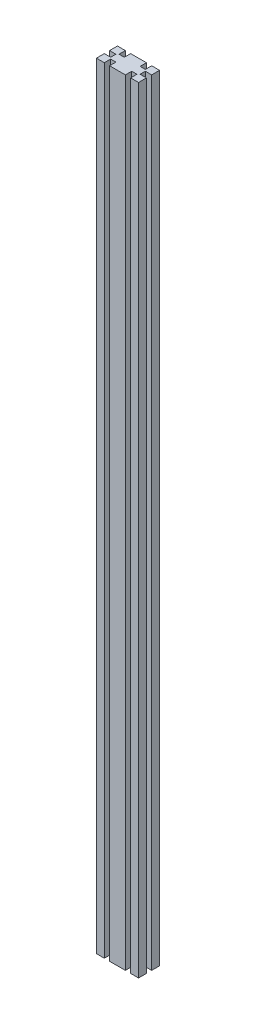
SolidWorks part; units mm, degrees
ref_plane "Front Plane" through (0, 0, 0) normal (0, 0, 1) x (1, 0, 0)
ref_plane "Top Plane" through (0, 0, 0) normal (0, 1, 0) x (1, 0, 0)
ref_plane "Right Plane" through (0, 0, 0) normal (1, 0, 0) x (0, 0, -1)
sketch "Sketch1" plane through (0, 0, 0) normal (0, 1, 0) x (1, 0, 0)
  line L1 (-20, -10) -> (20, -10)
  line L2 (-20, -10) -> (-20, 10)
  line L3 (-20, 10) -> (20, 10)
  line L4 (20, -10) -> (20, 10)
  line L5 (-20, -10) -> (20, 10) construction
  line L6 (-20, 10) -> (20, -10) construction
  point P0 (0, 0)
  dimension "D1" = 20
  dimension "D2" = 40
extrude "Boss-Extrude1" add sketch "Sketch1" along normal blind 368.3 and the other way blind 368.3
sketch "Sketch2" plane through (0, 0, 0) normal (0, 1, 0) x (1, 0, 0)
  line L0 (-20, 10) -> (0, 10) construction
  line L1 (20, 10) -> (-20, 10) construction
  line L2 (0, 10) -> (20, 10) construction
  line L4 (-20, 10) -> (-20, -10) construction
  line L5 (-12.5, 4) -> (-7.5, 4)
  line L6 (-12.5, 4) -> (-12.5, 16)
  line L7 (-12.5, 16) -> (-7.5, 16)
  line L8 (-7.5, 4) -> (-7.5, 16)
  line L9 (-12.5, 4) -> (-7.5, 16) construction
  line L10 (-12.5, 16) -> (-7.5, 4) construction
  line L11 (-14, 2.5) -> (-26, 2.5)
  line L12 (-14, 2.5) -> (-14, -2.5)
  line L13 (-14, -2.5) -> (-26, -2.5)
  line L14 (-26, 2.5) -> (-26, -2.5)
  line L15 (-14, 2.5) -> (-26, -2.5) construction
  line L16 (-14, -2.5) -> (-26, 2.5) construction
  line L17 (-55, 0) -> (55, 0) construction
  line L18 (-14, 2.5) -> (-26, -2.5) construction
  line L19 (-14, -2.5) -> (-26, 2.5) construction
  line L20 (-12.5, -16) -> (-7.5, -4) construction
  line L21 (-12.5, -4) -> (-7.5, -16) construction
  line L22 (-14, 2.5) -> (-26, 2.5)
  line L23 (-14, -2.5) -> (-26, -2.5)
  line L24 (-7.5, -4) -> (-7.5, -16)
  line L25 (-12.5, -16) -> (-7.5, -16)
  line L26 (-12.5, -4) -> (-12.5, -16)
  line L27 (-12.5, -4) -> (-7.5, -4)
  line L28 (0, -55) -> (0, 55) construction
  line L29 (12.5, -4) -> (7.5, -16) construction
  line L30 (12.5, -16) -> (7.5, -4) construction
  line L31 (14, -2.5) -> (26, 2.5) construction
  line L32 (14, 2.5) -> (26, -2.5) construction
  line L33 (14, -2.5) -> (26, 2.5) construction
  line L34 (14, 2.5) -> (26, -2.5) construction
  line L35 (12.5, 16) -> (7.5, 4) construction
  line L36 (12.5, 4) -> (7.5, 16) construction
  line L37 (20, 10) -> (0, 10) construction
  line L38 (12.5, -4) -> (7.5, -4)
  line L39 (12.5, -4) -> (12.5, -16)
  line L40 (12.5, -16) -> (7.5, -16)
  line L41 (7.5, -4) -> (7.5, -16)
  line L42 (14, -2.5) -> (26, -2.5)
  line L43 (14, 2.5) -> (26, 2.5)
  line L44 (26, 2.5) -> (26, -2.5)
  line L45 (14, -2.5) -> (26, -2.5)
  line L46 (14, 2.5) -> (14, -2.5)
  line L47 (14, 2.5) -> (26, 2.5)
  line L48 (7.5, 4) -> (7.5, 16)
  line L49 (12.5, 16) -> (7.5, 16)
  line L50 (12.5, 4) -> (12.5, 16)
  line L51 (12.5, 4) -> (7.5, 4)
  point P7 (-10, 10)
  point P12 (-20, 0)
  point P25 (-10, -10)
  point P40 (10, -10)
  point P41 (20, 0)
  point P42 (10, 10)
  dimension "D1" = 12
  dimension "D2" = 5
  dimension "D3" = 5
  dimension "D4" = 12
extrude "Cut-Extrude1" cut sketch "Sketch2" against normal through all both and the other way through all contours L5 L8 L7 L6 | L27 L26 L25 L24 | L11 L14 L13 L12 | L51 L50 L49 L48 | L43 L46 L42 L44 | L38 L41 L40 L39
